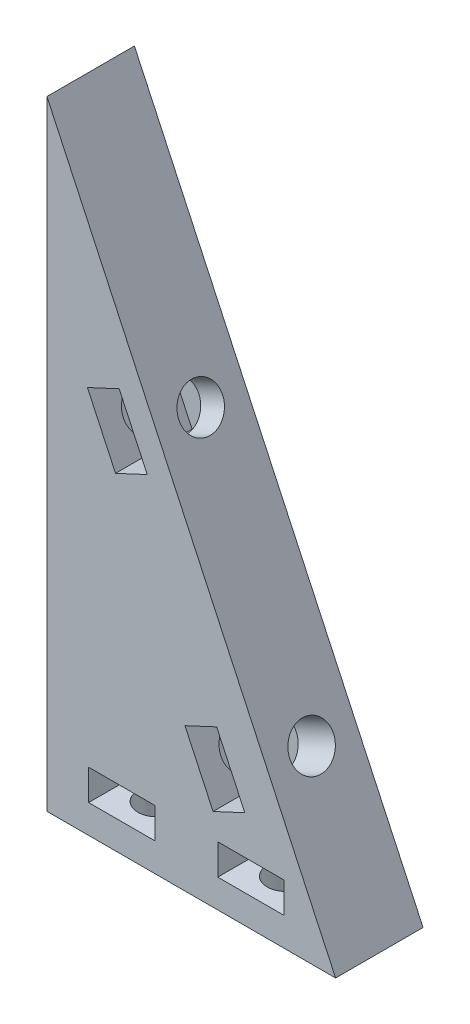
SolidWorks part; units mm, degrees
ref_plane "Front" through (0, 0, 0) normal (0, 0, 1) x (1, 0, 0)
ref_plane "Top" through (0, 0, 0) normal (0, 1, 0) x (1, 0, 0)
ref_plane "Right" through (0, 0, 0) normal (1, 0, 0) x (0, 0, -1)
sketch "Sketch1" plane through (0, 0, 0) normal (0, 0, 1) x (1, 0, 0)
  line L0 (0, 70.7687) -> (0, 0)
  line L1 (0, 0) -> (33, 0)
  line L2 (33, 0) -> (0, 70.7687)
  dimension "D1" = 33
  dimension "D2" = 65
extrude "Boss-Extrude1" add sketch "Sketch1" along normal blind 10
sketch "Sketch2" plane through (0, 0, 0) normal (0, -1, 0) x (-1, 0, 0)
  line L0 (-16.5, -10) -> (-16.5, 0) construction
  line L1 (-13.6, -6.9) -> (-19.4, -6.9)
  line L2 (-13.6, -6.9) -> (-13.6, -3.1)
  line L3 (-13.6, -3.1) -> (-19.4, -3.1)
  line L4 (-19.4, -6.9) -> (-19.4, -3.1)
  line L5 (-13.6, -6.9) -> (-19.4, -3.1) construction
  line L6 (-13.6, -3.1) -> (-19.4, -6.9) construction
  line L7 (0, -10) -> (-33, -10) construction
  line L8 (0, 0) -> (-33, 0) construction
  line L9 (0, -5) -> (-33, -5) construction
  line L10 (0, -10) -> (0, 0) construction
  line L11 (-33, -10) -> (-33, 0) construction
  point P0 (-16.5, -5)
  point P18 (-16.5, -5)
  dimension "D1" = 5.8
  dimension "D2" = 3.8
extrude "Boss-Extrude2" add sketch "Sketch2" along normal blind 2
sketch "Sketch3" plane through (0, 0, 0) normal (0, -1, 0) x (-1, 0, 0)
  line L3 (0, -10) -> (-33, -10) construction
  line L4 (-33, -10) -> (-33, 0) construction
  circle A2 centre (-23.33, -6) radius 2.15
  circle A3 centre (-8.55, -6) radius 2.15
  dimension "D1" = 4.3
  dimension "D2" = 4
  dimension "D3" = 9.67
  dimension "D4" = 14.78
  dimension "D5" = 4
extrude "Cut-Extrude1" cut sketch "Sketch3" against normal blind 12
sketch "Sketch4" plane through (0, 0, 0) normal (0, 0, -1) x (-1, 0, 0)
  line L0 (-27.13, 3.2517) -> (-27.13, 5) construction
  line L1 (-25.4815, -1.25) -> (-21.1815, -1.25) construction
  line L2 (-19.53, 3.2517) -> (-19.53, 5) construction
  line L3 (-25.48, 0) -> (-21.18, 0)
  line L4 (-21.18, 0) -> (-10.7, 0) construction
  line L5 (-15.94, 0) -> (-15.94, 7.9966) construction
  line L7 (-12.35, 3.2517) -> (-12.35, 5) construction
  line L8 (-25.4815, 0) -> (-25.4815, -2.5) construction
  line L13 (-23.33, 5) -> (-23.33, -5) construction
  line L14 (-35.3315, -5) -> (66.6685, -5) construction
  line L15 (-21.1815, -2.5) -> (-21.1815, 0) construction
  line L20 (-27.13, 3.2517) -> (-19.53, 3.2517)
  line L21 (-19.53, 3.2517) -> (-19.53, 6.7517)
  line L22 (-19.53, 6.7517) -> (-27.13, 6.7517)
  line L23 (-27.13, 6.7517) -> (-27.13, 3.2517)
  line L24 (-27.13, 5) -> (-19.53, 5) construction
  line L25 (-4.75, 3.2517) -> (-4.75, 5) construction
  line L26 (-4.75, 6.7517) -> (-4.75, 3.2517)
  line L27 (-12.35, 6.7517) -> (-4.75, 6.7517)
  line L28 (-12.35, 3.2517) -> (-12.35, 6.7517)
  line L29 (-4.75, 3.2517) -> (-12.35, 3.2517)
  point P5 (-23.33, 0)
  dimension "D1" = 7.6
  dimension "D2" = 3.8
  dimension "D3" = 3.5
extrude "Cut-Extrude5" cut sketch "Sketch4" along normal blind 8.75 from surface at -10 contours L23 L20 L21 L22 starting at face at (11, 23.5896, 10)
sketch "Sketch7" plane through (0, 0, 10) normal (0, 0, 1) x (1, 0, 0)
  line L0 (19.53, 6.7517) -> (19.53, 3.2517)
  line L1 (19.53, 3.2517) -> (27.13, 3.2517)
  line L2 (27.13, 3.2517) -> (27.13, 6.7517)
  line L3 (27.13, 6.7517) -> (19.53, 6.7517)
  line L4 (23.33, 3.2517) -> (23.33, 0)
  line L5 (0, 0) -> (33, 0) construction
  line L6 (23.33, 0) -> (15.949, 0)
  line L8 (15.949, 0) -> (15.949, 7.1074) construction
  line L9 (4.7679, 6.7517) -> (12.3679, 6.7517)
  line L10 (4.7679, 3.2517) -> (4.7679, 6.7517)
  line L11 (12.3679, 3.2517) -> (4.7679, 3.2517)
  line L12 (12.3679, 6.7517) -> (12.3679, 3.2517)
extrude "Cut-Extrude6" cut sketch "Sketch7" against normal blind 8.75 contours L12 L9 L10 L11
sketch "Sketch10" plane through (0, 0, 10) normal (0, 0, 1) x (1, 0, 0)
  line L0 (0, 70.7687) -> (12.5813, 43.7879)
  line L1 (33, 0) -> (0, 70.7687) construction
  line L2 (0, 70.7687) -> (25.2599, 16.5987)
  line L3 (25.2599, 16.5987) -> (-3.9859, 2.9612)
  line L4 (12.5813, 43.7879) -> (-12.9507, 31.8822)
  line L6 (8.2565, 45.9641) -> (4.6312, 44.2736)
  line L7 (4.6312, 44.2736) -> (7.8431, 37.3856)
  line L8 (7.8431, 37.3856) -> (11.4684, 39.0761)
  line L10 (8.2565, 45.9641) -> (11.4684, 39.0761)
  line L11 (21.0114, 14.6176) -> (19.4054, 18.0616)
  line L12 (19.4054, 18.0616) -> (15.7802, 16.3711)
  line L13 (15.7802, 16.3711) -> (18.9921, 9.4832)
  line L15 (21.0114, 14.6176) -> (22.6173, 11.1736)
  line L16 (22.6173, 11.1736) -> (18.9921, 9.4832)
  dimension "D1" = 3.8
  dimension "D2" = 29.77
  dimension "D3" = 59.77
  dimension "D4" = 90
  dimension "D5" = 7.6
  dimension "D6" = 4
  dimension "D7" = 3
  dimension "D8" = 90
  dimension "D9" = 180
  dimension "D10" = 7.6
  dimension "D11" = 3.8
  dimension "D12" = 4
extrude "Cut-Extrude7" cut sketch "Sketch10" against normal blind 8.75 contours L10 L6 L7 L4 | L10 L4 L7 L8 | L12 L13 L3 L11 | L16 L15 L3 L13
sketch "Sketch12" plane through (27.106, 12.6397, 0) normal (0.9063, 0.4226, 0) x (0, 0, -1)
  line L0 (-5, 64.1382) -> (-5, 34.3682) construction
  line L1 (-10, 64.1382) -> (0, 64.1382) construction
  line L2 (-5, 64.1382) -> (-5, 4.3682) construction
  circle A0 centre (-5, 34.3682) radius 2.5
  circle A1 centre (-5, 4.3682) radius 2.5
  dimension "D3" = 5
  dimension "D4" = 5
  dimension "D1" = 29.77
  dimension "D2" = 59.77
extrude "Cut-Extrude8" cut sketch "Sketch12" against normal blind 10
